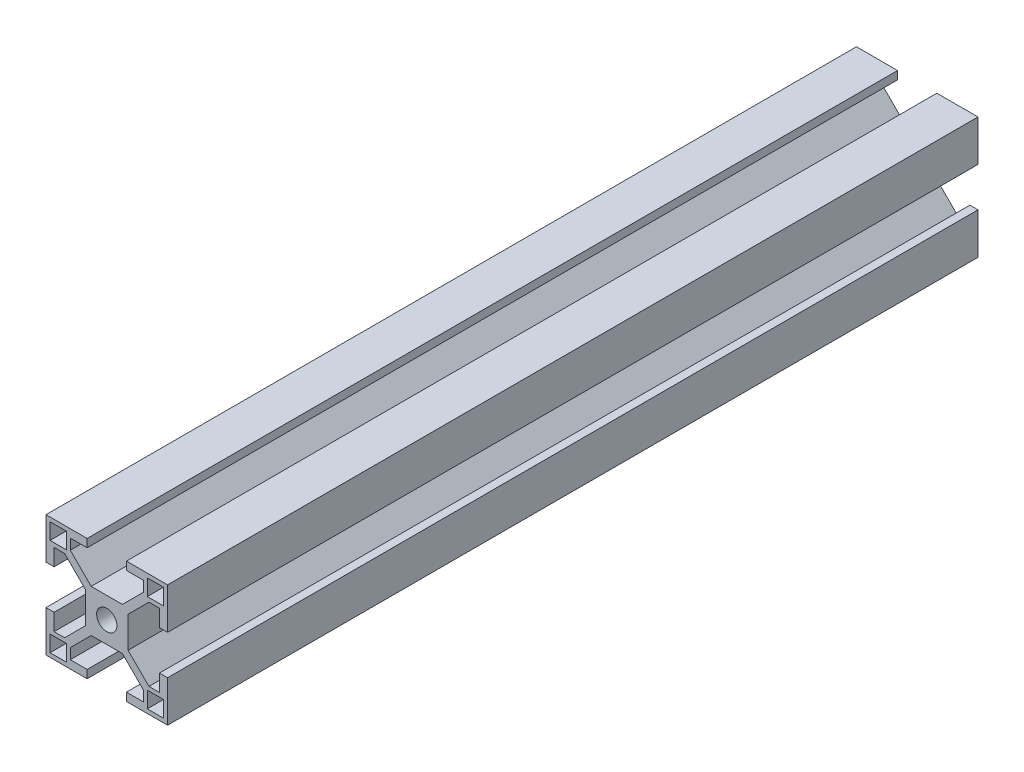
SolidWorks part; units mm, degrees
ref_plane "Front Plane" through (0, 0, 0) normal (0, 0, 1) x (1, 0, 0)
ref_plane "Top Plane" through (0, 0, 0) normal (0, 1, 0) x (1, 0, 0)
ref_plane "Right Plane" through (0, 0, 0) normal (1, 0, 0) x (0, 0, -1)
sketch "Sketch2" plane through (0, 0, 0) normal (0, 0, 1) x (1, 0, 0)
  line L0 (0, 0) -> (-38.5315, 38.5315) construction
  line L5 (-5.25, -5.25) -> (5.25, 5.25) construction
  line L6 (-5.25, 5.25) -> (5.25, -5.25) construction
  line L7 (0, 0) -> (-15, 0) construction
  line L8 (55, 0) -> (-55, 0) construction
  line L9 (-15, 0) -> (-15, 15) construction
  line L10 (-15, 15) -> (0, 15) construction
  line L11 (0, -55) -> (0, 55) construction
  line L12 (-10.4001, 9) -> (-5.25, 3.8499)
  line L13 (-15, 15) -> (-9, 15)
  line L14 (-15, 15) -> (-15, 9)
  line L18 (-15, 9) -> (-15, 4.85)
  line L19 (-15, 4.85) -> (-13, 4.85)
  line L20 (-13, 9) -> (-13, 4.85)
  line L21 (-9, 15) -> (-4.85, 15)
  line L23 (-9, 13) -> (-4.85, 13)
  line L24 (-4.85, 15) -> (-4.85, 13)
  line L25 (-9, 10.4001) -> (-3.8499, 5.25)
  line L26 (-13, 9) -> (-10.4001, 9)
  line L27 (-14, 14) -> (-10, 14)
  line L28 (-14, 14) -> (-14, 10)
  line L29 (-14, 10) -> (-10, 10)
  line L30 (-10, 14) -> (-10, 10)
  line L31 (-9, 13) -> (-9, 10.4001)
  line L32 (-5.25, 3.8499) -> (-5.25, 0)
  line L33 (-3.8499, 5.25) -> (0, 5.25)
  line L34 (15, 15) -> (9, 15)
  line L35 (15, 15) -> (15, 9)
  line L36 (15, 9) -> (15, 4.85)
  line L37 (13, 9) -> (13, 4.85)
  line L38 (15, 4.85) -> (13, 4.85)
  line L39 (13, 9) -> (10.4001, 9)
  line L40 (14, 10) -> (10, 10)
  line L41 (14, 14) -> (14, 10)
  line L42 (14, 14) -> (10, 14)
  line L43 (10, 14) -> (10, 10)
  line L44 (9, 13) -> (4.85, 13)
  line L45 (9, 13) -> (9, 10.4001)
  line L46 (9, 15) -> (4.85, 15)
  line L47 (4.85, 15) -> (4.85, 13)
  line L48 (9, 10.4001) -> (3.8499, 5.25)
  line L49 (10.4001, 9) -> (5.25, 3.8499)
  line L50 (5.25, 3.8499) -> (5.25, 0)
  line L51 (3.8499, 5.25) -> (0, 5.25)
  line L52 (15, -15) -> (15, -9)
  line L53 (15, -15) -> (9, -15)
  line L54 (9, -15) -> (4.85, -15)
  line L55 (9, -13) -> (4.85, -13)
  line L56 (4.85, -15) -> (4.85, -13)
  line L57 (9, -13) -> (9, -10.4001)
  line L58 (10, -14) -> (10, -10)
  line L59 (14, -14) -> (10, -14)
  line L60 (14, -14) -> (14, -10)
  line L61 (14, -10) -> (10, -10)
  line L62 (13, -9) -> (13, -4.85)
  line L63 (13, -9) -> (10.4001, -9)
  line L64 (15, -9) -> (15, -4.85)
  line L65 (15, -4.85) -> (13, -4.85)
  line L66 (10.4001, -9) -> (5.25, -3.8499)
  line L67 (9, -10.4001) -> (3.8499, -5.25)
  line L68 (3.8499, -5.25) -> (0, -5.25)
  line L69 (5.25, -3.8499) -> (5.25, 0)
  line L70 (-15, -15) -> (-9, -15)
  line L71 (-15, -15) -> (-15, -9)
  line L72 (-15, -9) -> (-15, -4.85)
  line L73 (-13, -9) -> (-13, -4.85)
  line L74 (-15, -4.85) -> (-13, -4.85)
  line L75 (-13, -9) -> (-10.4001, -9)
  line L76 (-14, -10) -> (-10, -10)
  line L77 (-14, -14) -> (-14, -10)
  line L78 (-14, -14) -> (-10, -14)
  line L79 (-10, -14) -> (-10, -10)
  line L80 (-9, -13) -> (-4.85, -13)
  line L81 (-9, -13) -> (-9, -10.4001)
  line L82 (-9, -15) -> (-4.85, -15)
  line L83 (-4.85, -15) -> (-4.85, -13)
  line L84 (-9, -10.4001) -> (-3.8499, -5.25)
  line L85 (-10.4001, -9) -> (-5.25, -3.8499)
  line L86 (-5.25, -3.8499) -> (-5.25, 0)
  line L87 (-3.8499, -5.25) -> (0, -5.25)
  circle A3 centre (0, 0) radius 2.5
  circle A4 centre (0, 0) radius 2.5 [skipped]
  circle A5 centre (0, 0) radius 2.5 [skipped]
  point P96 (0, 0)
  dimension "D1" = 15
  dimension "D2" = 2.5999
  dimension "D3" = 4.15
  dimension "D4" = 2
  dimension "D5" = 4.15
  dimension "D6" = 2
  dimension "D7" = 0.99
  dimension "D8" = 0.99
  dimension "D9" = 1
  dimension "D10" = 4
  dimension "D11" = 10.5
  dimension "D14" = 4
extrude "Boss-Extrude1" add sketch "Sketch2" along normal blind 200
